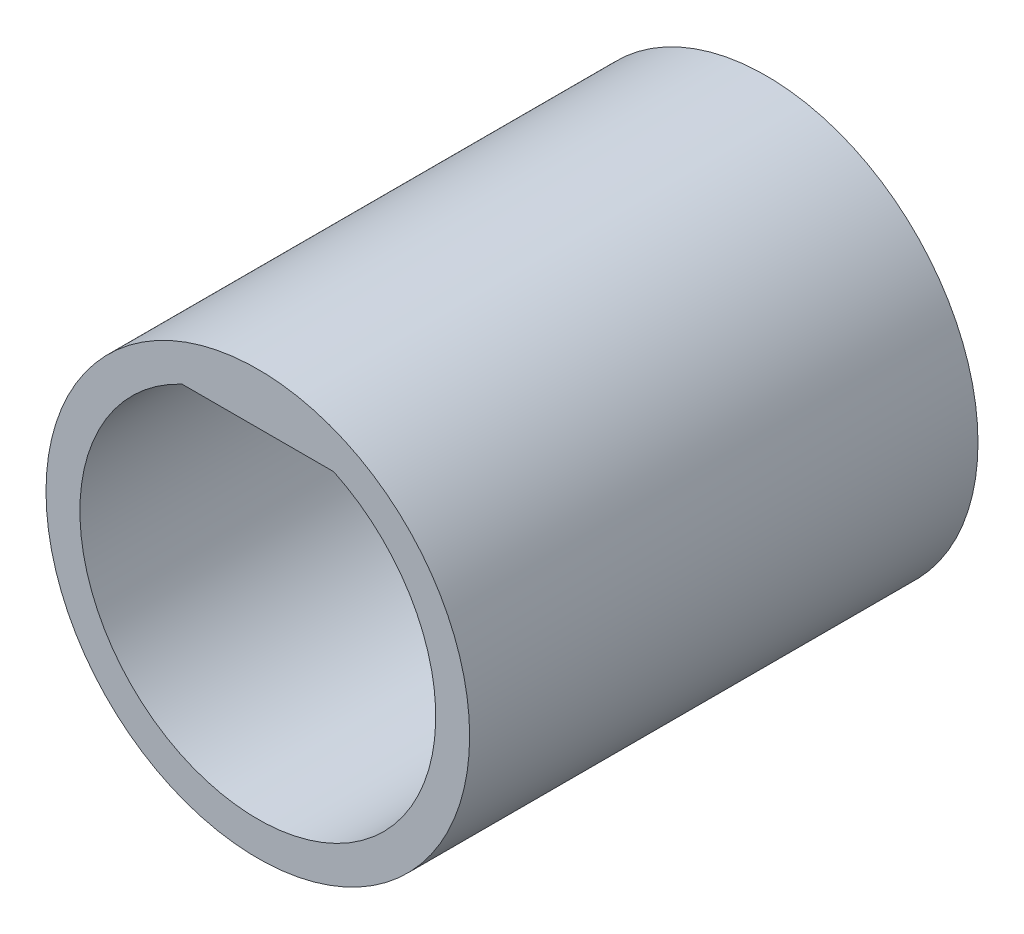
SolidWorks part; units mm, degrees
ref_plane "Front Plane" through (0, 0, 0) normal (0, 0, 1) x (1, 0, 0)
ref_plane "Top Plane" through (0, 0, 0) normal (0, 1, 0) x (1, 0, 0)
ref_plane "Right Plane" through (0, 0, 0) normal (1, 0, 0) x (0, 0, -1)
sketch "Sketch1" plane through (0, 0, 0) normal (0, 0, 1) x (1, 0, 0)
  line L0 (-1.1359, 2.413) -> (1.1359, 2.413)
  arc A0 (-1.1359, 2.413) -> (1.1359, 2.413) centre (0, 0) ccw
  circle A1 centre (0, 0) radius 3.175
  dimension "D1" = 5.334
  dimension "D3" = 6.35
  dimension "D2" = 2.413
extrude "Boss-Extrude1" add sketch "Sketch1" along normal blind 7.62
